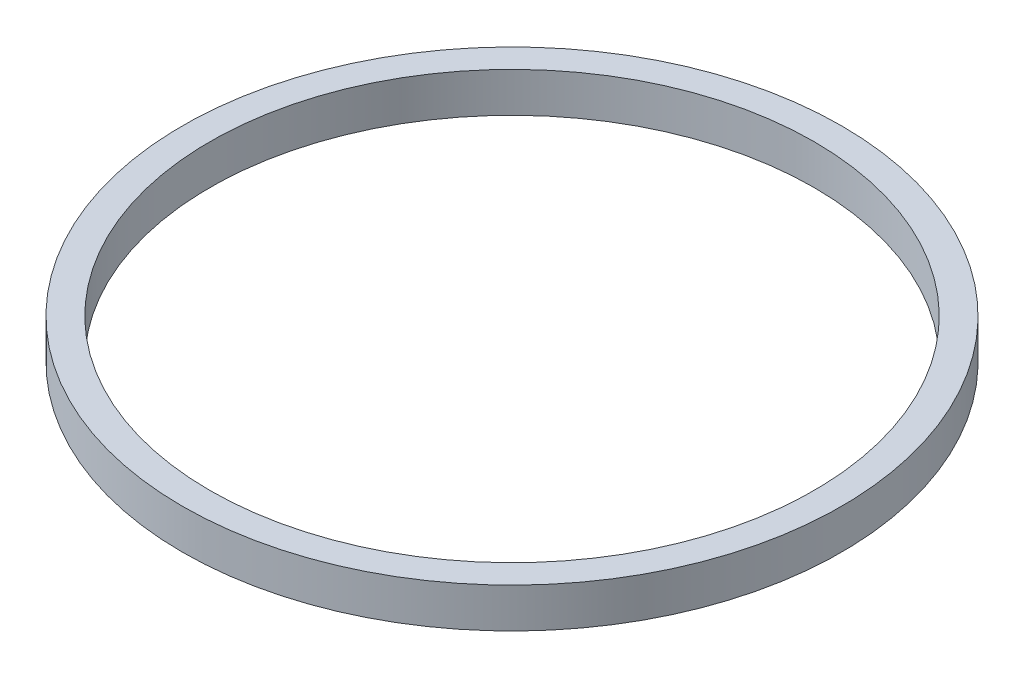
SolidWorks part; units mm, degrees
ref_plane "Front Plane" through (0, 0, 0) normal (0, 0, 1) x (1, 0, 0)
ref_plane "Top Plane" through (0, 0, 0) normal (0, 1, 0) x (1, 0, 0)
ref_plane "Right Plane" through (0, 0, 0) normal (1, 0, 0) x (0, 0, -1)
sketch "Sketch1" plane through (0, 0, 0) normal (0, 1, 0) x (1, 0, 0)
  circle A0 centre (0, 0) radius 27.5
  circle A1 centre (0, 0) radius 30
  dimension "D1" = 55
  dimension "D2" = 60
extrude "Boss-Extrude1" add sketch "Sketch1" along normal blind 3.62 contours A1
sketch "Sketch3" plane through (0, 3.62, 0) normal (0, 1, 0) x (1, 0, 0)
  circle A0 centre (0, 0) radius 27.5
  dimension "D1" = 55
extrude "Cut-Extrude1" cut sketch "Sketch3" against normal blind 3.62
